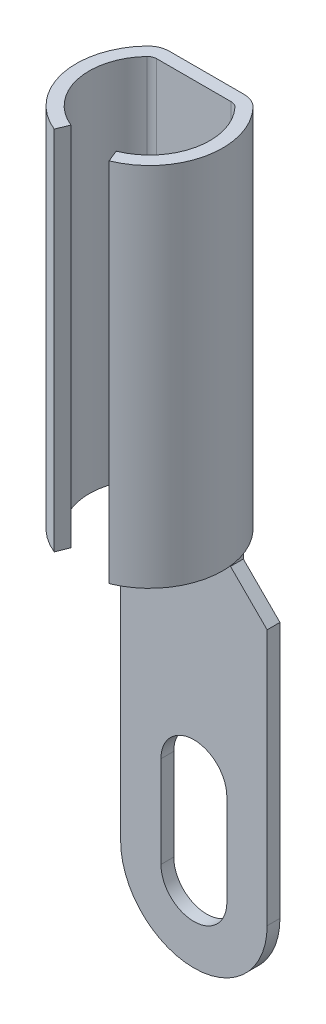
SolidWorks part; units mm, degrees
material "Pure Silver"
ref_plane "Front Plane" through (0, 0, 0) normal (0, 0, 1) x (1, 0, 0)
ref_plane "Top Plane" through (0, 0, 0) normal (0, 1, 0) x (1, 0, 0)
ref_plane "Right Plane" through (0, 0, 0) normal (1, 0, 0) x (0, 0, -1)
sketch "Sketch1" plane through (0, 0, 0) normal (0, 1, 0) x (1, 0, 0)
  line L0 (-1.0178, 1.5612) -> (1.0178, 1.5612)
  arc A0 (0.75, -1.854) -> (1.4541, 1.3732) centre (0, 0) ccw
  arc A1 (-1.4541, 1.3732) -> (-0.75, -1.854) centre (0, 0) ccw
  arc A2 (-1.4541, 1.3732) -> (-1.0178, 1.5612) centre (-1.0178, 0.9612) cw
  arc A3 (1.4541, 1.3732) -> (1.0178, 1.5612) centre (1.0178, 0.9612) ccw
  point P8 (-1.25, 1.5612)
  point P11 (1.25, 1.5612)
  dimension "D1" = 4
  dimension "D4" = 0.6
  dimension "D5" = 0.6
  dimension "D2" = 2.5
  dimension "D3" = 1.5
extrude "Extrude-Thin1" add sketch "Sketch1" along normal blind 10 thin
sketch "Sketch2" plane through (0, 0, -1.2112) normal (0, 0, 1) x (1, 0, 0)
  line L0 (-1, 0) -> (-1, -1)
  line L1 (55, 0) -> (-55, 0) construction
  line L2 (-1, -1) -> (-2, -2)
  line L3 (-2, -2) -> (-2, -9)
  line L4 (1, 0) -> (1, -1)
  line L5 (1, -1) -> (2, -2)
  line L6 (2, -2) -> (2, -9)
  line L7 (-1, 0) -> (1, 0)
  line L8 (0, -55) -> (0, 55) construction
  line L9 (0.9, -9) -> (0.9, -6.5)
  line L10 (-0.9, -6.5) -> (-0.9, -9)
  arc A0 (-2, -9) -> (2, -9) centre (0, -9) ccw
  arc A1 (-0.9, -9) -> (0.9, -9) centre (0, -9) ccw
  arc A2 (0.9, -6.5) -> (-0.9, -6.5) centre (0, -6.5) ccw
  dimension "D3" = 2
  dimension "D7" = 0.9
  dimension "D1" = 2
  dimension "D2" = 1
  dimension "D4" = 1
  dimension "D5" = 9
  dimension "D6" = 2.5
extrude "Extrude1" add sketch "Sketch2" against normal blind 0.35
